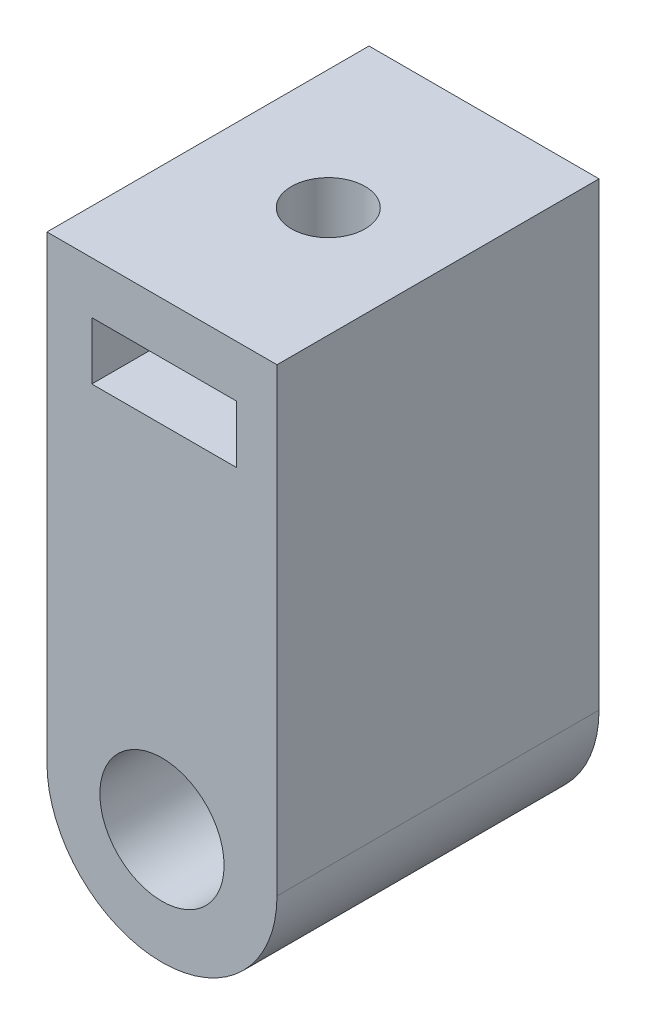
SolidWorks part; units mm, degrees
ref_plane "Спереди" through (0, 0, 0) normal (0, 0, 1) x (1, 0, 0)
ref_plane "Сверху" through (0, 0, 0) normal (0, 1, 0) x (1, 0, 0)
ref_plane "Справа" through (0, 0, 0) normal (1, 0, 0) x (0, 0, -1)
sketch "Эскиз1" plane through (0, 0, 0) normal (0, 0, 1) x (1, 0, 0)
  circle A0 centre (0, 0) radius 2.7
  circle A1 centre (0, 0) radius 5
extrude "Бобышка-Вытянуть1" add sketch "Эскиз1" along normal blind 14
sketch "Эскиз2" plane through (0, 0, 14) normal (0, 0, 1) x (1, 0, 0)
  line L0 (-5, 0) -> (-2.7, 0)
  line L2 (-5, 0) -> (-5, 20)
  line L3 (-5, 20) -> (5, 20)
  line L4 (5, 0) -> (5, 20)
  line L5 (0.6548, 2.6194) -> (5, 20) construction
  line L6 (-5, 20) -> (-0.6548, 2.6194) construction
  line L7 (2.7, 0) -> (5, 0)
  arc A0 (2.7, 0) -> (-2.7, 0) centre (0, 0) ccw
  point P0 (0, 0)
  point P9 (0, 0)
extrude "Бобышка-Вытянуть2" add sketch "Эскиз2" against normal up to surface (14 mm away) up to face at (5, 0, 0)
sketch "Эскиз5" plane through (0, 0, 14) normal (0, 0, 1) x (1, 0, 0)
  line L1 (3.25, 17.75) -> (-3.05, 17.75)
  line L2 (3.25, 17.75) -> (3.25, 15.25)
  line L3 (3.25, 15.25) -> (-3.05, 15.25)
  line L4 (-3.05, 17.75) -> (-3.05, 15.25)
  line L5 (3.25, 17.75) -> (-3.05, 15.25) construction
  line L6 (3.25, 15.25) -> (-3.05, 17.75) construction
  point P0 (0.1, 16.5)
extrude "Вырез-Вытянуть3" cut sketch "Эскиз5" against normal blind 10
sketch "Эскиз8" plane through (0, 15.25, 0) normal (0, 1, 0) x (1, 0, 0)
  line L0 (-3.05, -14) -> (-5.0865, -14)
sketch "Эскиз10" plane through (-5, 0, 0) normal (-1, 0, 0) x (0, 0, 1)
  line L0 (12.5, 3.2685) -> (14, 3.2685) construction
  line L1 (1.4417, 2.925) -> (12.5, 2.925)
  line L2 (1.4417, 2.925) -> (1.4417, 12.975)
  line L3 (1.4417, 12.975) -> (12.5, 12.975)
  line L4 (12.5, 2.925) -> (12.5, 12.975)
  line L5 (1.4417, 2.925) -> (12.5, 12.975) construction
  line L6 (1.4417, 12.975) -> (12.5, 2.925) construction
  line L7 (14, 20) -> (14, 0) construction
  line L8 (6.9709, 7.95) -> (12.5, 7.95) construction
  line L9 (6.9709, 2.925) -> (14, 2.925) construction
  line L10 (0, 0) -> (0, 20) construction
  point P0 (6.9709, 7.95)
  dimension "D1" = 1.4417
extrude "Вырез-Вытянуть5" cut sketch "Эскиз10" against normal blind 9.4
sketch "Эскиз12" plane through (0, 2.925, 0) normal (0, 1, 0) x (1, 0, 0)
  line L0 (0.1995, -1.4417) -> (0.1995, -12.5) construction
  line L1 (4.4, -1.4417) -> (-5, -1.4417) construction
  line L2 (4.4, -12.5) -> (-5, -12.5) construction
  line L3 (-5, -6.9709) -> (4.4, -6.9709) construction
  line L4 (-5, -1.4417) -> (-5, -12.5) construction
  line L5 (4.4, -1.4417) -> (4.4, -12.5) construction
  circle A0 centre (0.1995, -6.9709) radius 1.6
extrude "Вырез-Вытянуть7" cut sketch "Эскиз12" along normal through all
sketch "Эскиз13" plane through (0, 15.25, 0) normal (0, 1, 0) x (1, 0, 0)
  line L0 (-1.3858, -4.2257) -> (-1.3858, -4)
  line L1 (3.3695, -6.9706) -> (1.7842, -4.2254)
  line L2 (1.7842, -4.2254) -> (-1.3858, -4.2257)
  line L3 (-1.3858, -4.2257) -> (-2.9705, -6.9711)
  line L4 (-2.9705, -6.9711) -> (-1.3853, -9.7163)
  line L5 (-1.3853, -9.7163) -> (1.7847, -9.716)
  line L6 (1.7847, -9.716) -> (3.3695, -6.9706)
  line L7 (3.25, -4) -> (-3.05, -4) construction
  line L8 (3.3308, -6.9706) -> (3.3695, -6.9706)
  circle A0 centre (0.1995, -6.9709) radius 3.17 construction
